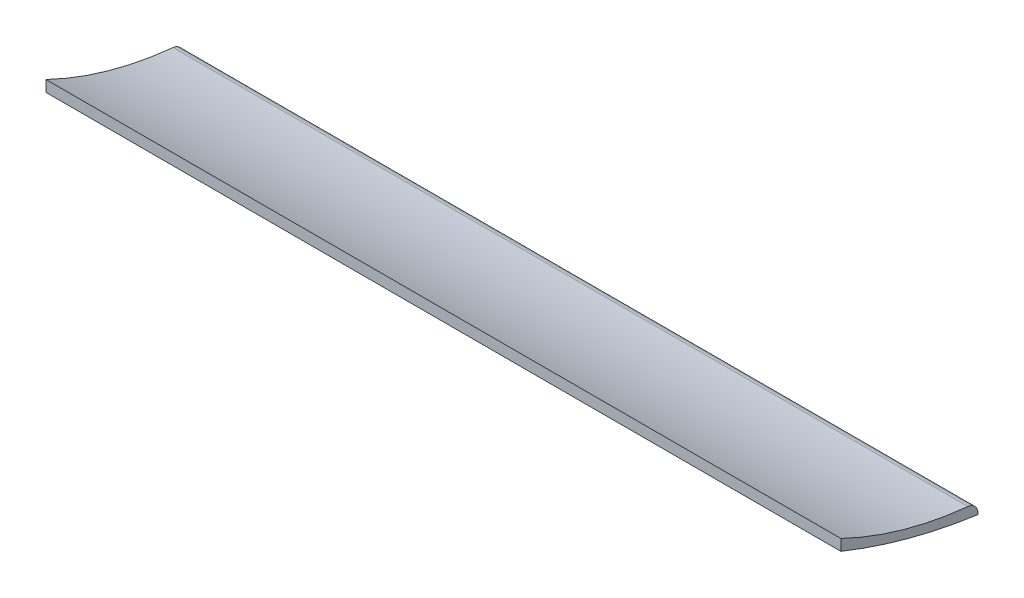
SolidWorks part; units mm, degrees
material "Rubber"
ref_plane "Front Plane" through (0, 0, 0) normal (0, 0, 1) x (1, 0, 0)
ref_plane "Top Plane" through (0, 0, 0) normal (0, 1, 0) x (1, 0, 0)
ref_plane "Right Plane" through (0, 0, 0) normal (1, 0, 0) x (0, 0, -1)
sketch "Sketch1" plane through (0, 0, 0) normal (1, 0, 0) x (0, 0, -1)
  line L0 (0, 0) -> (122.6726, -32.87) construction
  line L1 (0, 0) -> (32.6753, 0) construction
  line L2 (122.6726, -32.87) -> (122.6726, -22.87)
  line L4 (0, 10) -> (0, 0)
  arc A0 (0, 10) -> (122.6726, -22.87) centre (147.7864, 316.2012) ccw
  arc A1 (0, 0) -> (122.6726, -32.87) centre (194.9149, 482.0873) ccw
  dimension "D3" = 340
  dimension "D4" = 520
  dimension "D1" = 127
  dimension "D2" = 15
  dimension "D5" = 10
extrude "Boss-Extrude1" add sketch "Sketch1" along normal blind 711.2
fillet "Fillet1" radius 10 1 edges at (355.6, -22.87, -122.6726)
ref_plane "Plane1" through (355.6, 0, 0) normal (1, 0, 0) x (0, 0, -1)
